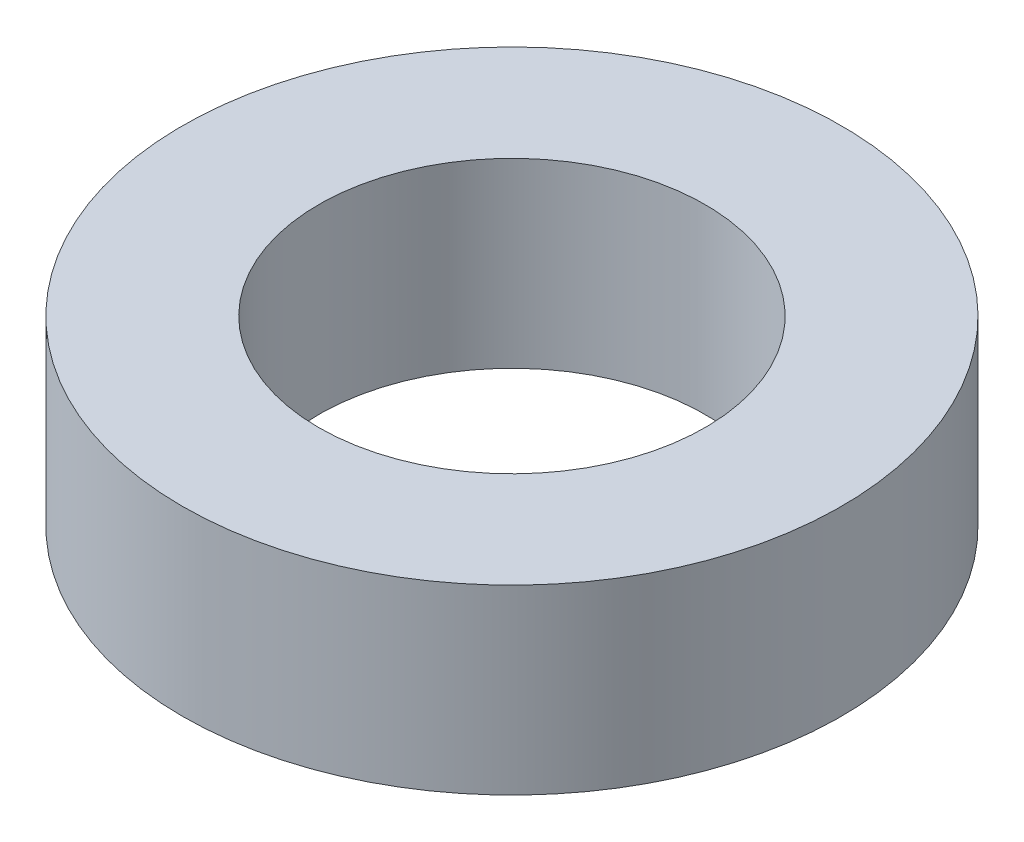
SolidWorks part; units mm, degrees
ref_plane "Front Plane" through (0, 0, 0) normal (0, 0, 1) x (1, 0, 0)
ref_plane "Top Plane" through (0, 0, 0) normal (0, 1, 0) x (1, 0, 0)
ref_plane "Right Plane" through (0, 0, 0) normal (1, 0, 0) x (0, 0, -1)
sketch "Sketch1" plane through (0, 0, 0) normal (0, 1, 0) x (1, 0, 0)
  circle A0 centre (0, 0) radius 7.25
  circle A1 centre (0, 0) radius 4.25
  dimension "D1" = 8.5
  dimension "D2" = 14.5
extrude "Boss-Extrude1" add sketch "Sketch1" along normal blind 4
